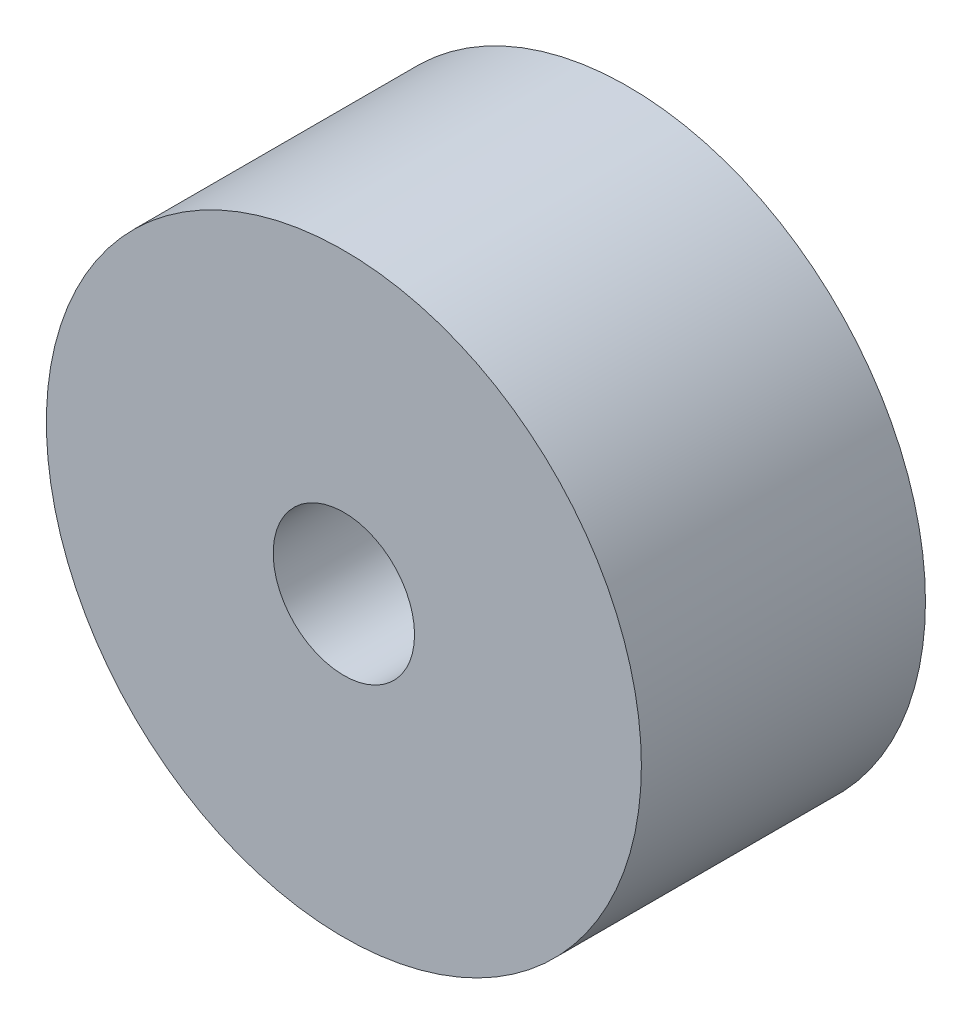
SolidWorks part; units mm, degrees
ref_plane "Front Plane" through (0, 0, 0) normal (0, 0, 1) x (1, 0, 0)
ref_plane "Top Plane" through (0, 0, 0) normal (0, 1, 0) x (1, 0, 0)
ref_plane "Right Plane" through (0, 0, 0) normal (1, 0, 0) x (0, 0, -1)
sketch "Sketch1" plane through (0, 0, 0) normal (0, 0, 1) x (1, 0, 0)
  circle A0 centre (0, 0) radius 21.05
  circle A1 centre (0, 0) radius 5
  dimension "D1" = 42.1
  dimension "D2" = 10
extrude "Boss-Extrude1" add sketch "Sketch1" along normal mid plane 20.1
